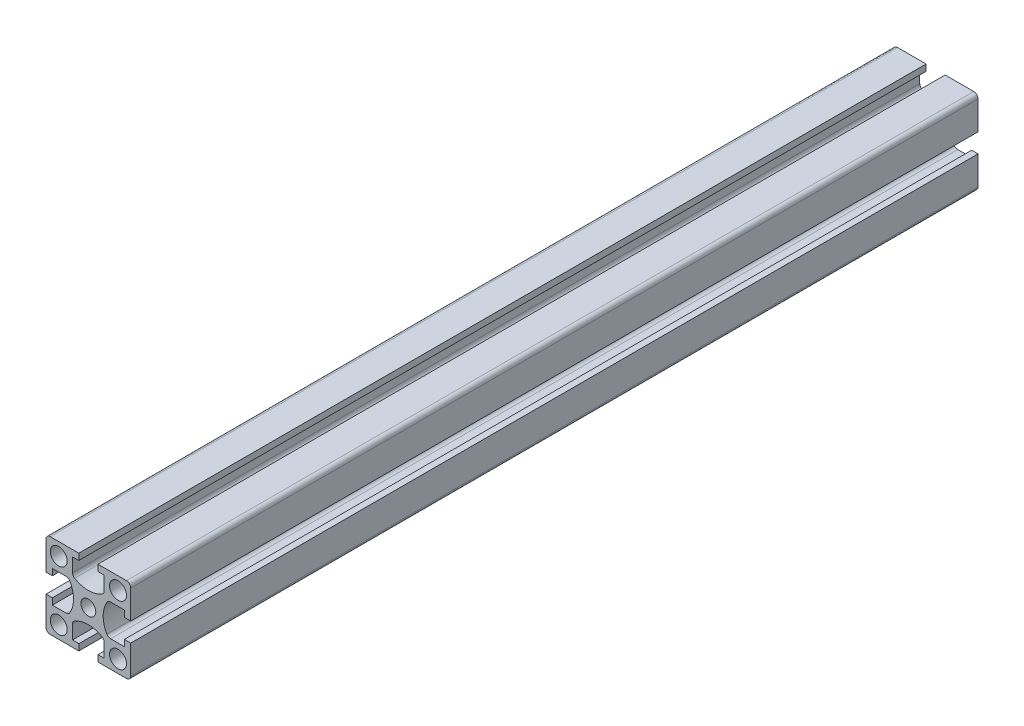
SolidWorks part; units mm, degrees
ref_plane "Front Plane" through (0, 0, 0) normal (0, 0, 1) x (1, 0, 0)
ref_plane "Top Plane" through (0, 0, 0) normal (0, 1, 0) x (1, 0, 0)
ref_plane "Right Plane" through (0, 0, 0) normal (1, 0, 0) x (0, 0, -1)
sketch "Sketch1" plane through (0, 0, 0) normal (0, 0, 1) x (1, 0, 0)
  line L64 (-10, 9) -> (-10, 2.25)
  line L65 (-10, 2.25) -> (-8.5, 2.25)
  line L66 (-8.5, 2.25) -> (-8.5, 3.75)
  line L67 (-8.5, 3.75) -> (-5.2369, 3.75)
  line L68 (-5.2369, -3.75) -> (-8.5, -3.75)
  line L69 (-8.5, -3.75) -> (-8.5, -2.25)
  line L70 (-8.5, -2.25) -> (-10, -2.25)
  line L71 (-10, -2.25) -> (-10, -9)
  line L72 (-9, -10) -> (-2.25, -10)
  line L73 (-2.25, -10) -> (-2.25, -8.5)
  line L74 (-2.25, -8.5) -> (-3.75, -8.5)
  line L75 (-3.75, -8.5) -> (-3.75, -5.2369)
  line L76 (3.75, -5.2369) -> (3.75, -8.5)
  line L77 (3.75, -8.5) -> (2.25, -8.5)
  line L78 (2.25, -8.5) -> (2.25, -10)
  line L79 (2.25, -10) -> (9, -10)
  line L80 (10, -9) -> (10, -2.25)
  line L81 (10, -2.25) -> (8.5, -2.25)
  line L82 (8.5, -2.25) -> (8.5, -3.75)
  line L83 (8.5, -3.75) -> (5.2369, -3.75)
  line L84 (5.2369, 3.75) -> (8.5, 3.75)
  line L85 (8.5, 3.75) -> (8.5, 2.25)
  line L86 (8.5, 2.25) -> (10, 2.25)
  line L87 (10, 2.25) -> (10, 9)
  line L88 (9, 10) -> (2.25, 10)
  line L89 (2.25, 10) -> (2.25, 8.5)
  line L90 (2.25, 8.5) -> (3.75, 8.5)
  line L91 (3.75, 8.5) -> (3.75, 5.2369)
  line L92 (-3.75, 5.2369) -> (-3.75, 8.5)
  line L93 (-3.75, 8.5) -> (-2.25, 8.5)
  line L94 (-2.25, 8.5) -> (-2.25, 10)
  line L95 (-2.25, 10) -> (-9, 10)
  circle A5 centre (-7, -7) radius 2
  circle A6 centre (7, -7) radius 2
  circle A7 centre (7, 7) radius 2
  circle A8 centre (0, 0) radius 1.75
  circle A9 centre (-7, 7) radius 2
  arc A32 (-9, 10) -> (-10, 9) centre (-9, 9) ccw
  arc A33 (-4.3708, 3.25) -> (-5.2369, 3.75) centre (-5.2369, 2.75) ccw
  arc A34 (-4.3708, -3.25) -> (-4.3708, 3.25) centre (-10, 0) ccw
  arc A35 (-5.2369, -3.75) -> (-4.3708, -3.25) centre (-5.2369, -2.75) ccw
  arc A36 (-10, -9) -> (-9, -10) centre (-9, -9) ccw
  arc A37 (-3.25, -4.3708) -> (-3.75, -5.2369) centre (-2.75, -5.2369) ccw
  arc A38 (3.25, -4.3708) -> (-3.25, -4.3708) centre (0, -10) ccw
  arc A39 (3.75, -5.2369) -> (3.25, -4.3708) centre (2.75, -5.2369) ccw
  arc A40 (9, -10) -> (10, -9) centre (9, -9) ccw
  arc A41 (4.3708, -3.25) -> (5.2369, -3.75) centre (5.2369, -2.75) ccw
  arc A42 (4.3708, 3.25) -> (4.3708, -3.25) centre (10, 0) ccw
  arc A43 (5.2369, 3.75) -> (4.3708, 3.25) centre (5.2369, 2.75) ccw
  arc A44 (10, 9) -> (9, 10) centre (9, 9) ccw
  arc A45 (3.25, 4.3708) -> (3.75, 5.2369) centre (2.75, 5.2369) ccw
  arc A46 (-3.25, 4.3708) -> (3.25, 4.3708) centre (0, 10) ccw
  arc A47 (-3.75, 5.2369) -> (-3.25, 4.3708) centre (-2.75, 5.2369) ccw
extrude "Boss-Extrude1" add sketch "Sketch1" along normal blind 200
